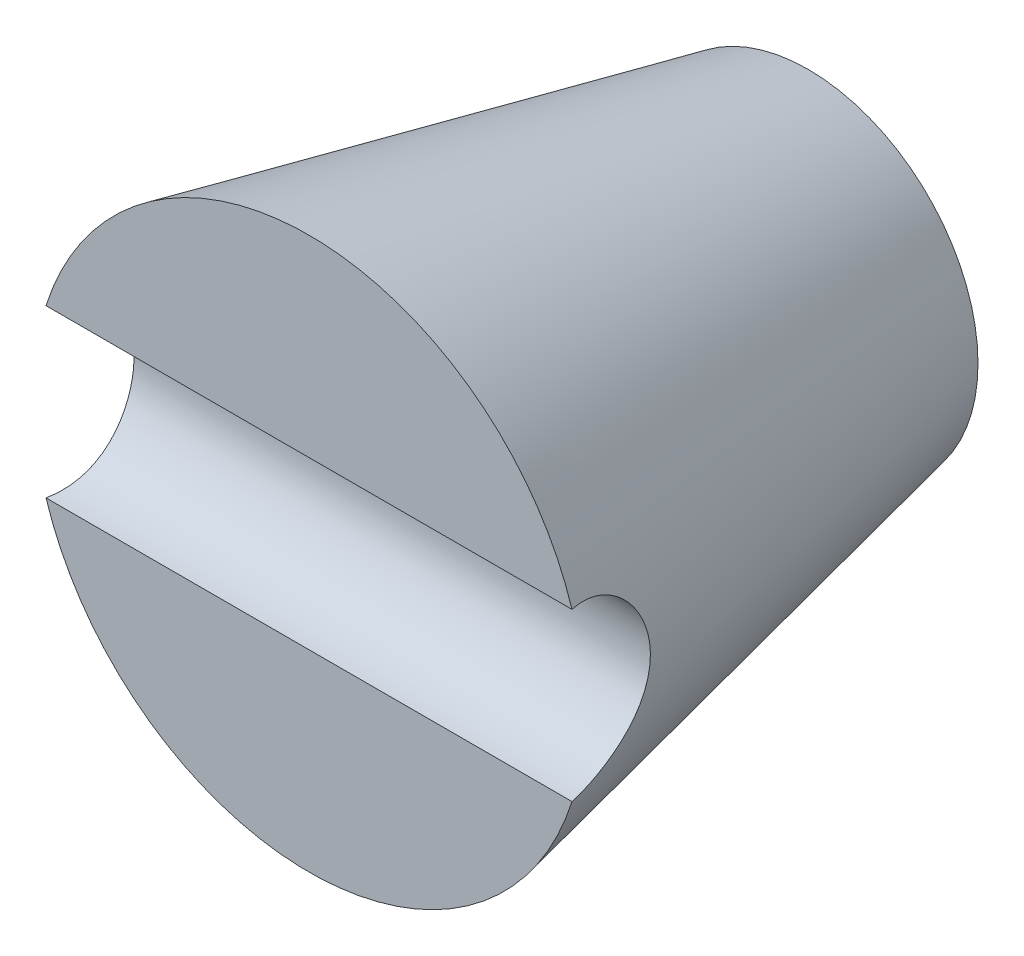
SolidWorks part; units mm, degrees
ref_plane "Front Plane" through (0, 0, 0) normal (0, 0, 1) x (1, 0, 0)
ref_plane "Top Plane" through (0, 0, 0) normal (0, 1, 0) x (1, 0, 0)
ref_plane "Right Plane" through (0, 0, 0) normal (1, 0, 0) x (0, 0, -1)
sketch "Sketch1" plane through (0, 0, 0) normal (0, 0, 1) x (1, 0, 0)
  circle A0 centre (0, 0) radius 30.595
  dimension "D1" = 61.19
extrude "Boss-Extrude1" add sketch "Sketch1" along normal blind 90 draft 12 draft outward yes
sketch "Sketch2" plane through (0, 0, 0) normal (0, 0, -1) x (-1, 0, 0)
  circle A0 centre (0, 0) radius 15
  dimension "D1" = 30
extrude "Cut-Extrude1" cut sketch "Sketch2" against normal blind 50
sketch "Sketch3" plane through (0, 0, 0) normal (1, 0, 0) x (0, 0, -1)
  line L0 (0, 0) -> (-90, 0) construction
  line L1 (-90, 49.7251) -> (-90, -49.7251) construction
  circle A0 centre (-90, 0) radius 15
  dimension "D1" = 30
extrude "Cut-Extrude4" cut sketch "Sketch3" against normal through all and the other way through all
